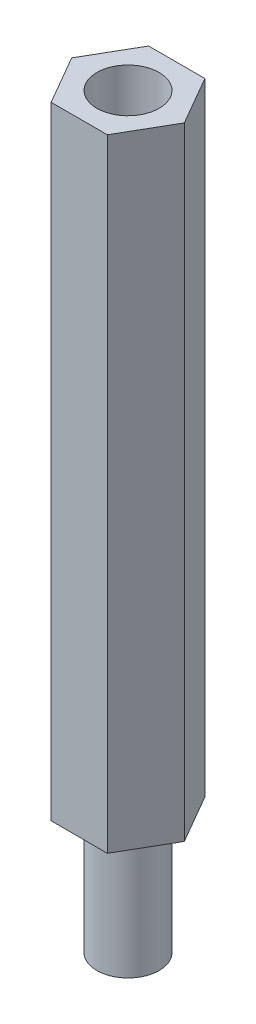
SolidWorks part; units mm, degrees
material "Медь"
ref_plane "Спереди" through (0, 0, 0) normal (0, 0, 1) x (1, 0, 0)
ref_plane "Сверху" through (0, 0, 0) normal (0, 1, 0) x (1, 0, 0)
ref_plane "Справа" through (0, 0, 0) normal (1, 0, 0) x (0, 0, -1)
sketch "Эскиз1" plane through (0, 0, 0) normal (0, 1, 0) x (1, 0, 0)
  line L1 (1.3568, -2.35) -> (2.7135, 0)
  line L2 (2.7135, 0) -> (1.3568, 2.35)
  line L3 (1.3568, 2.35) -> (-1.3568, 2.35)
  line L4 (-1.3568, 2.35) -> (-2.7135, 0)
  line L5 (-2.7135, 0) -> (-1.3568, -2.35)
  line L6 (-1.3568, -2.35) -> (1.3568, -2.35)
  circle A0 centre (0, 0) radius 2.35 construction
  dimension "D1" = 4.7
extrude "Бобышка-Вытянуть1" add sketch "Эскиз1" along normal blind 30
sketch "Эскиз2" plane through (0, 0, 0) normal (0, -1, 0) x (1, 0, 0)
  circle A0 centre (0, 0) radius 1.5
  dimension "D1" = 3
extrude "Бобышка-Вытянуть2" add sketch "Эскиз2" along normal blind 6
sketch "Эскиз3" plane through (0, 30, 0) normal (0, 1, 0) x (1, 0, 0)
  circle A0 centre (0, 0) radius 1.5
  dimension "D1" = 3
extrude "Вырез-Вытянуть1" cut sketch "Эскиз3" against normal offset from surface (24 mm away) 6 up to face at (0, 0, 1.5)
